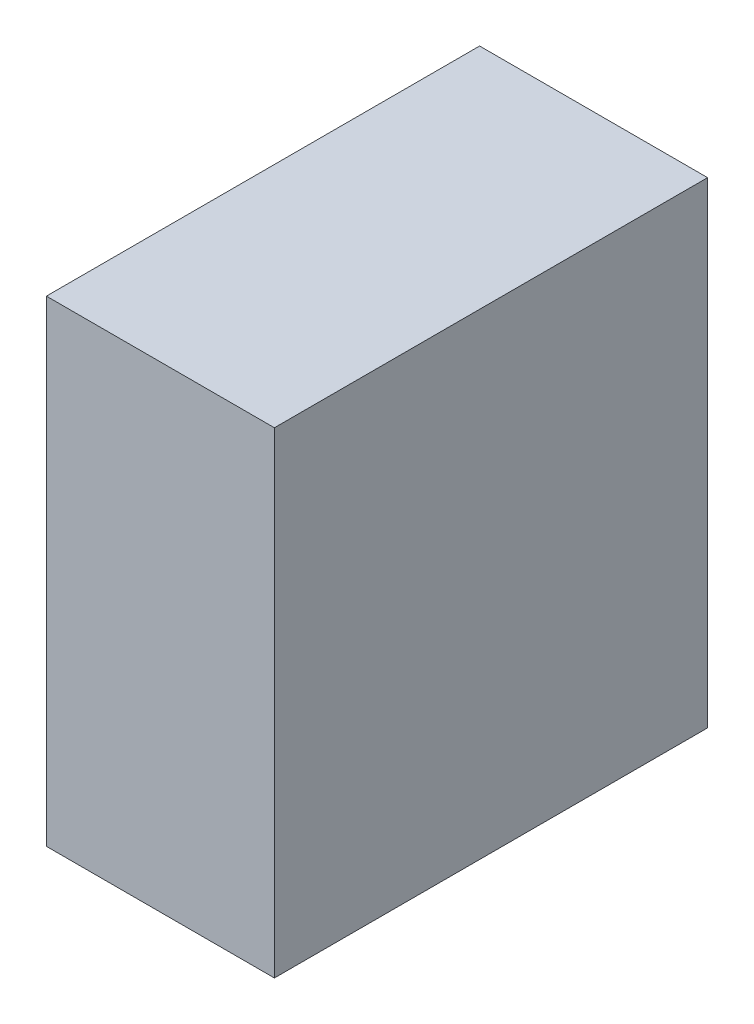
SolidWorks part; units mm, degrees
ref_plane "Front Plane" through (0, 0, 0) normal (0, 0, 1) x (1, 0, 0)
ref_plane "Top Plane" through (0, 0, 0) normal (0, 1, 0) x (1, 0, 0)
ref_plane "Right Plane" through (0, 0, 0) normal (1, 0, 0) x (0, 0, -1)
other "Configuration Table"
sketch "Sketch1" plane through (0, 0, 0) normal (0, 0, 1) x (1, 0, 0)
  line L1 (150, 1044) -> (550, 1044)
  line L2 (150, 1044) -> (150, 1880)
  line L3 (150, 1880) -> (550, 1880)
  line L4 (550, 1044) -> (550, 1880)
extrude "PACK_blank_yigini_525_adet_1" add sketch "Sketch1" against normal blind 760 from offset 30 separate body
